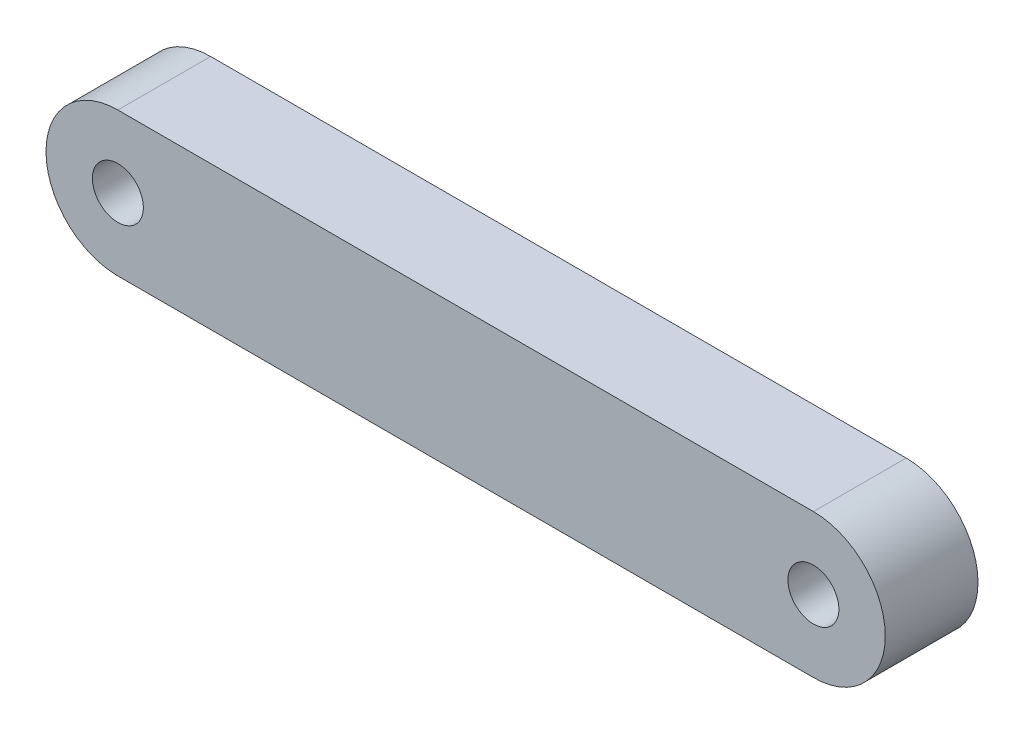
SolidWorks part; units mm, degrees
ref_plane "Front Plane" through (0, 0, 0) normal (0, 0, 1) x (1, 0, 0)
ref_plane "Top Plane" through (0, 0, 0) normal (0, 1, 0) x (1, 0, 0)
ref_plane "Right Plane" through (0, 0, 0) normal (1, 0, 0) x (0, 0, -1)
sketch "Sketch1" plane through (0, 0, 0) normal (0, 0, 1) x (1, 0, 0)
  line L0 (0, 3.1) -> (30, 3.1)
  line L1 (0, -3.1) -> (30, -3.1)
  circle A0 centre (0, 0) radius 1.1
  arc A1 (0, 3.1) -> (0, -3.1) centre (0, 0) ccw
  arc A2 (30, -3.1) -> (30, 3.1) centre (30, 0) ccw
  circle A3 centre (30, 0) radius 1.1
  circle A5 centre (0, 0) radius 3.1 construction
  point P8 (3.1, 0)
  dimension "D1" = 2.2
  dimension "D4" = 2.2
  dimension "D3" = 30
  dimension "D2" = 2
extrude "Boss-Extrude1" add sketch "Sketch1" along normal blind 4
